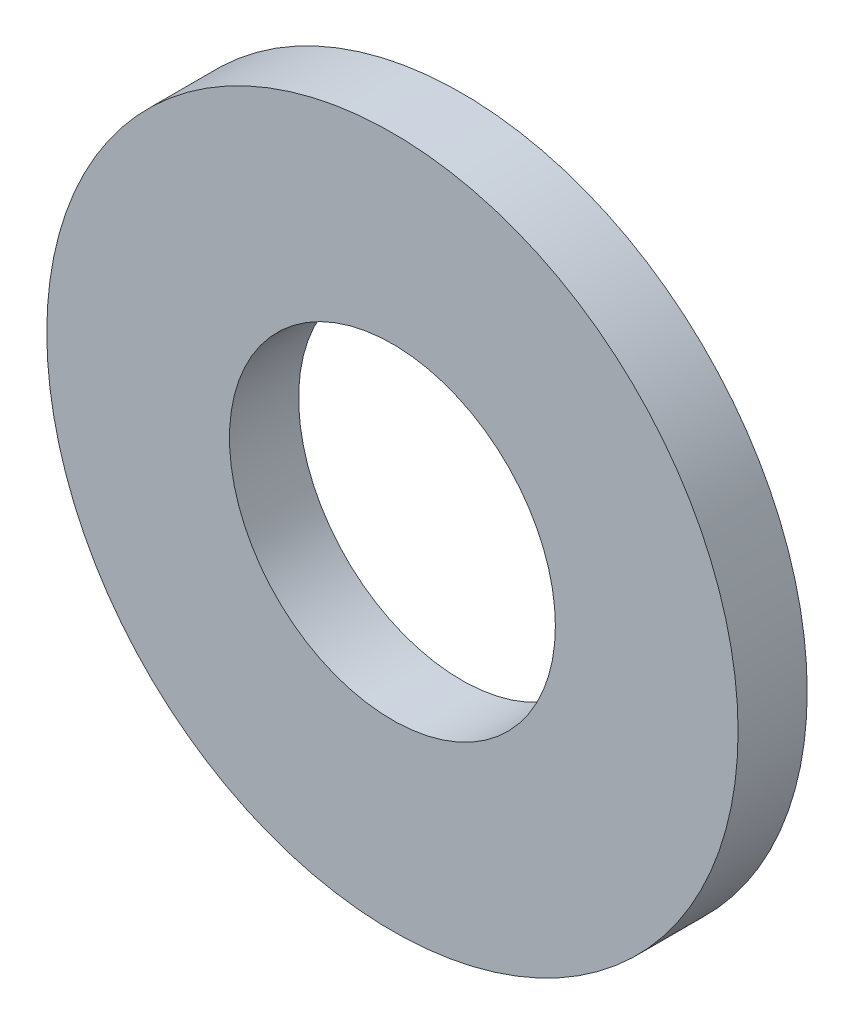
SolidWorks part; units mm, degrees
ref_plane "Plano frontal" through (0, 0, 0) normal (0, 0, 1) x (1, 0, 0)
ref_plane "Plano superior" through (0, 0, 0) normal (0, 1, 0) x (1, 0, 0)
ref_plane "Plano direito" through (0, 0, 0) normal (1, 0, 0) x (0, 0, -1)
sketch "Esboço1" plane through (0, 0, 0) normal (0, 0, 1) x (1, 0, 0)
  circle A0 centre (0, 0) radius 1.65
  circle A1 centre (0, 0) radius 3.5
extrude "Ressalto-extrusão1" add sketch "Esboço1" along normal blind 0.7
